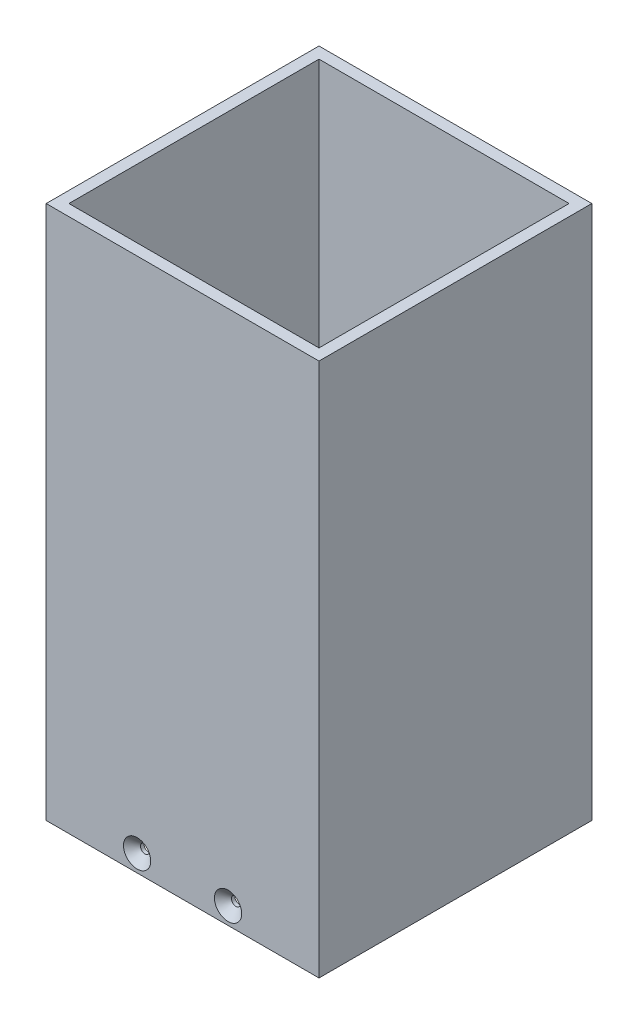
SolidWorks part; units mm, degrees
material "6061-T6 (SS)"
ref_plane "Front Plane" through (0, 0, 0) normal (0, 0, 1) x (1, 0, 0)
ref_plane "Top Plane" through (0, 0, 0) normal (0, 1, 0) x (1, 0, 0)
ref_plane "Right Plane" through (0, 0, 0) normal (1, 0, 0) x (0, 0, -1)
sketch "Sketch1" plane through (0, 0, 0) normal (0, 1, 0) x (1, 0, 0)
  line L1 (-38.1, -38.1) -> (38.1, -38.1)
  line L2 (-38.1, -38.1) -> (-38.1, 38.1)
  line L3 (-38.1, 38.1) -> (38.1, 38.1)
  line L4 (38.1, -38.1) -> (38.1, 38.1)
  line L5 (-38.1, -38.1) -> (38.1, 38.1) construction
  line L6 (-38.1, 38.1) -> (38.1, -38.1) construction
  line L7 (-34.925, -34.925) -> (34.925, -34.925)
  line L8 (-34.925, -34.925) -> (-34.925, 34.925)
  line L9 (-34.925, 34.925) -> (34.925, 34.925)
  line L10 (34.925, -34.925) -> (34.925, 34.925)
  line L11 (-34.925, -34.925) -> (34.925, 34.925) construction
  line L12 (-34.925, 34.925) -> (34.925, -34.925) construction
  point P0 (0, 0)
  point P6 (0, 0)
  dimension "D1" = 76.2
  dimension "D2" = 76.2
  dimension "D3" = 3.175
extrude "Boss-Extrude1" add sketch "Sketch1" along normal blind 9.525
sketch "Sketch2" plane through (0, 0, 38.1) normal (0, 0, 1) x (1, 0, 0)
  line L0 (-38.1, 0) -> (38.1, 0) construction
  circle A0 centre (-12.7, 4.7625) radius 1.2637
  circle A1 centre (12.7, 4.7625) radius 1.2637
  dimension "D4" = 2.5273
  dimension "D1" = 4.7625
  dimension "D2" = 12.7
  dimension "D3" = 12.7
extrude "Cut-Extrude1" cut sketch "Sketch2" against normal through all
chamfer "Chamfer1" distance 2.54 angle 41 4 edges at (-11.4363, 4.7625, -38.1) (13.9636, 4.7625, -38.1) (13.9636, 4.7625, 38.1) (-11.4363, 4.7625, 38.1)
sketch "Sketch3" plane through (0, 9.525, 0) normal (0, 1, 0) x (1, 0, 0)
  line L0 (-34.925, 34.925) -> (-34.925, -34.925) construction
  line L1 (-34.925, -34.925) -> (34.925, -34.925) construction
  line L2 (34.925, 34.925) -> (-34.925, 34.925) construction
  line L3 (34.925, -34.925) -> (34.925, 34.925) construction
  line L4 (38.1, -38.1) -> (38.1, 38.1)
  line L5 (38.1, 38.1) -> (-38.1, 38.1)
  line L6 (-38.1, 38.1) -> (-38.1, -38.1)
  line L7 (-38.1, -38.1) -> (38.1, -38.1)
  line L8 (38.1, -38.1) -> (38.1, 38.1)
  line L9 (38.1, 38.1) -> (-38.1, 38.1)
  line L10 (-38.1, 38.1) -> (-38.1, -38.1)
  line L11 (-38.1, -38.1) -> (38.1, -38.1)
  line L12 (-34.925, 34.925) -> (-34.925, -34.925)
  line L13 (-34.925, -34.925) -> (34.925, -34.925)
  line L14 (34.925, 34.925) -> (-34.925, 34.925)
  line L15 (34.925, -34.925) -> (34.925, 34.925)
  dimension "D1" = 0
extrude "Boss-Extrude2" add sketch "Sketch3" along normal blind 139.7
equation "\"D3@Sketch2\"=\"D2@Sketch2\""
equation "\"D1@Sketch1\"=\"D2@Sketch1\""
